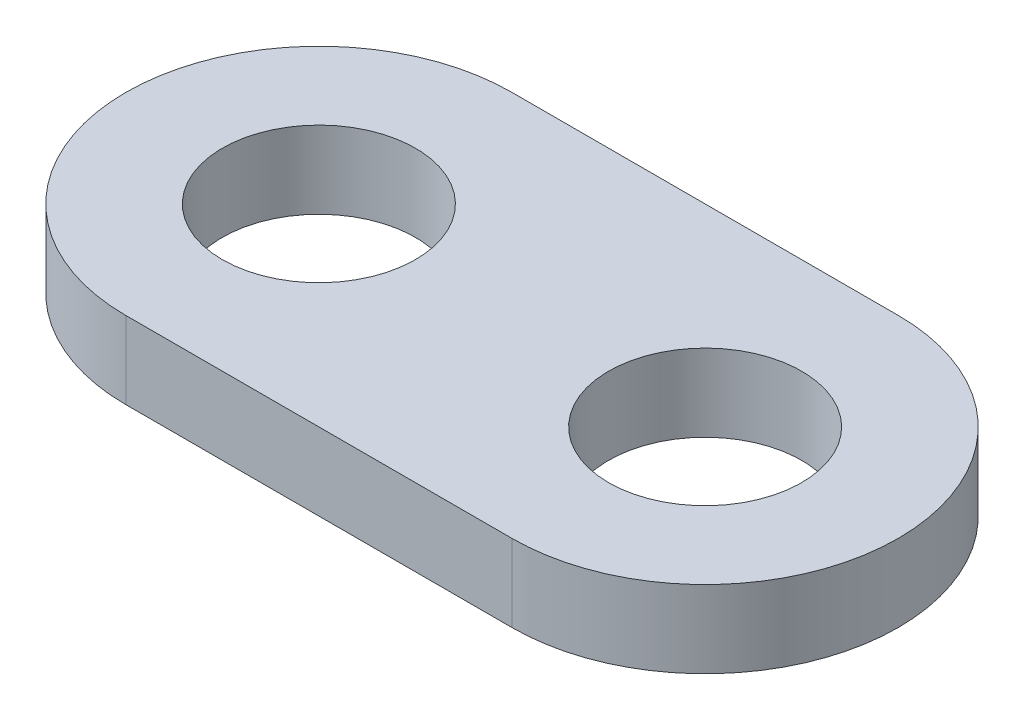
SolidWorks part; units mm, degrees
ref_plane "Front Plane" through (0, 0, 0) normal (0, 0, 1) x (1, 0, 0)
ref_plane "Top Plane" through (0, 0, 0) normal (0, 1, 0) x (1, 0, 0)
ref_plane "Right Plane" through (0, 0, 0) normal (1, 0, 0) x (0, 0, -1)
sketch "Sketch1" plane through (0, 0, 0) normal (0, 1, 0) x (1, 0, 0)
  line L0 (-6.35, -6.35) -> (6.35, -6.35)
  line L2 (6.35, -6.35) -> (6.35, 6.35) construction
  line L3 (6.35, 6.35) -> (-6.35, 6.35)
  line L4 (-6.35, -6.35) -> (-6.35, 6.35) construction
  line L5 (6.35, -6.35) -> (-6.35, 6.35) construction
  line L6 (6.35, 6.35) -> (-6.35, -6.35) construction
  arc A0 (-6.35, 6.35) -> (-6.35, -6.35) centre (-6.35, 0) ccw
  arc A1 (6.35, 6.35) -> (6.35, -6.35) centre (6.35, 0) cw
  point P0 (0, 0)
  point P10 (0, 0)
  dimension "D1" = 12.7
  dimension "D2" = 12.7
extrude "Boss-Extrude1" add sketch "Sketch1" along normal blind 2.54
sketch "Sketch2" plane through (0, 2.54, 0) normal (0, 1, 0) x (1, 0, 0)
  circle A0 centre (-6.35, 0) radius 3.175
  arc A1 (-6.35, 6.35) -> (-6.35, -6.35) centre (-6.35, 0) ccw construction
  circle A2 centre (6.35, 0) radius 3.175
  arc A3 (6.35, -6.35) -> (6.35, 6.35) centre (6.35, 0) ccw construction
  dimension "D1" = 6.35
extrude "Cut-Extrude1" cut sketch "Sketch2" against normal through all
